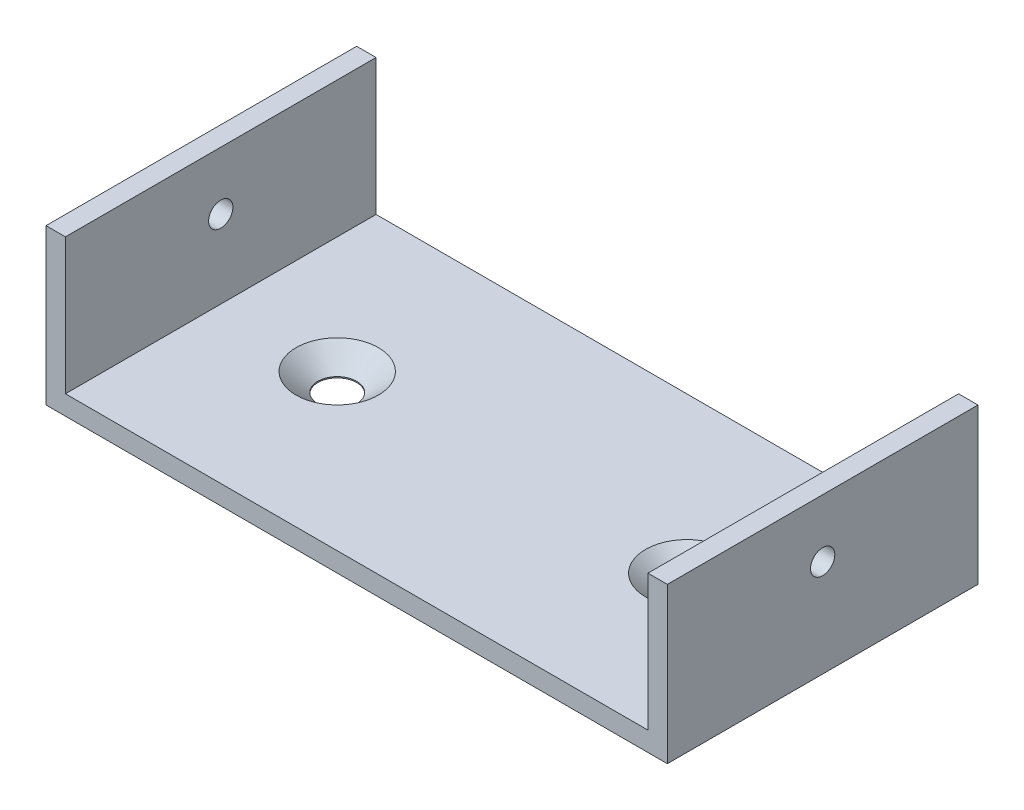
SolidWorks part; units mm, degrees
ref_plane "Front" through (0, 0, 0) normal (0, 0, 1) x (1, 0, 0)
ref_plane "Top" through (0, 0, 0) normal (0, 1, 0) x (1, 0, 0)
ref_plane "Right" through (0, 0, 0) normal (1, 0, 0) x (0, 0, -1)
sketch "Sketch1" plane through (0, 0, 0) normal (0, 0, 1) x (1, 0, 0)
  line L0 (0, -12.7) -> (0, 12.7) construction
  line L1 (-50.8, 0) -> (50.8, 0) construction
  line L2 (47.625, 12.7) -> (-47.625, 12.7) construction
  line L3 (-50.8, -12.7) -> (50.8, -12.7)
  line L4 (-50.8, -12.7) -> (-50.8, 12.7)
  line L5 (-50.8, 12.7) -> (50.8, 12.7)
  line L6 (50.8, -12.7) -> (50.8, 12.7)
  line L7 (-50.8, -12.7) -> (50.8, 12.7) construction
  line L8 (-50.8, 12.7) -> (50.8, -12.7) construction
  line L9 (-47.625, -12.7) -> (47.625, -12.7)
  point P3 (0, 0)
  point P4 (0, 0)
  point P8 (0, 0)
  point P13 (50.8, -9.525)
  point P17 (0, 12.7)
  point P20 (0, -12.7)
  dimension "Outside Width" = 101.6
  dimension "Outside Height" = 25.4
  dimension "Inside Height" = 22.225
  dimension "Wall Thickness" = 3.175
  dimension "Inside Width" = 95.25
sketch "Sketch2" plane through (0, 0, 0) normal (1, 0, 0) x (0, 0, -1)
  line L0 (-25.4, 0) -> (25.4, 0) construction
  dimension "Length" = 50.8
sketch "Sketch3" plane through (0, 0, 0) normal (0, 0, 1) x (1, 0, 0)
  line L0 (-50.8, 12.7) -> (-50.8, -12.7)
  line L1 (-50.8, -12.7) -> (50.8, -12.7)
  line L2 (50.8, -12.7) -> (50.8, 12.7)
  line L3 (50.8, 12.7) -> (47.625, 12.7)
  line L4 (47.625, 12.7) -> (47.625, -9.525)
  line L5 (47.625, -9.525) -> (-47.625, -9.525)
  line L6 (-47.625, -9.525) -> (-47.625, 12.7)
  line L7 (-47.625, 12.7) -> (-50.8, 12.7)
  line L8 (-47.625, -9.525) -> (-47.625, -12.7) construction
  dimension "D1" = 25.4
  dimension "D2" = 101.6
  dimension "D3" = 3.175
extrude "Boss-Extrude2" add sketch "Sketch3" along normal mid plane 50.8
sketch "Reference Sketch1" plane through (0, 0, 0) normal (1, 0, 0) x (0, 0, -1)
  line L0 (-25.4, 0) -> (25.4, 0) construction
  point P0 (19.05, 0)
  point P1 (-19.05, 0)
  dimension "D1" = 44.45
  dimension "D2" = 44.45
sketch "Sketch4" plane through (0, -9.525, 0) normal (0, 1, 0) x (1, 0, 0)
  line L0 (-47.625, 0) -> (-28.575, 0)
  line L1 (-47.625, -25.4) -> (-47.625, 25.4) construction
  line L2 (47.625, 0) -> (28.575, 0)
  line L3 (47.625, -25.4) -> (47.625, 25.4) construction
hole_wizard "1/4 (0.25) Diameter Hole1" positions "Sketch5" profile "Sketch6" hole size "1/4" standard "ANSI Inch" end condition through all
sketch "Sketch5" plane through (0, -9.525, 0) normal (0, 1, 0) x (1, 0, 0)
  point P0 (-28.575, 0)
  point P3 (28.575, 0)
sketch "Sketch6" plane through (-28.575, -9.525, 0) normal (1, 0, 0) x (0, 0, 1)
  line L0 (0, 0) -> (0, 3.175)
  line L1 (0, 3.175) -> (3.175, 3.175)
  line L2 (3.175, 3.175) -> (3.175, 2.9838)
  line L3 (3.175, 2.9838) -> (6.731, 0)
  line L5 (6.731, 0) -> (0, 0)
  line L6 (-3.175, 2.9838) -> (-6.731, 0) construction
  line L11 (0, -6.35) -> (0, 107.95) construction
  dimension "Thru Hole Dia." = 6.35
  dimension "Thru Hole Depth" = 3.175
  dimension "Near C'Sink Dia." = 13.462
  dimension "Near C'Sink Angle" = 100
sketch "Sketch7" plane through (50.8, 0, 0) normal (1, 0, 0) x (0, 0, -1)
  line L0 (0, -9.4842) -> (0, 3.2158)
hole_wizard "5/32 (0.15625) Diameter Hole1" positions "Sketch8" profile "Sketch9" hole size "5/32" standard "ANSI Inch" end condition through all
sketch "Sketch8" plane through (50.8, 0, 0) normal (1, 0, 0) x (0, 0, -1)
  point P0 (0, 3.2158)
sketch "Sketch9" plane through (50.8, 3.2158, 0) normal (0, 1, 0) x (0, 0, -1)
  line L0 (0, 0) -> (0, 101.6)
  line L1 (0, 101.6) -> (1.9844, 101.6)
  line L2 (1.9844, 101.6) -> (1.9844, 0)
  line L5 (1.9844, 0) -> (0, 0)
  line L11 (0, -6.35) -> (0, 107.95) construction
  dimension "Thru Hole Dia." = 3.9688
  dimension "Thru Hole Depth" = 101.6
equation "\"D1@Sketch3\" = \"Outside Height@Sketch1\""
equation "\"D2@Sketch3\" = \"Outside Width@Sketch1\""
equation "\"D3@Sketch3\" = \"Wall Thickness@Sketch1\""
equation "\"D1@Reference Sketch1\"=\"Outside Height@Sketch1\" * 1.75"
equation "\"D2@Reference Sketch1\" = \"D1@Reference Sketch1\""
equation "\"D1@Boss-Extrude2\" = \"Length@Sketch2\""
equation "\"Inside Height@Sketch1\"=\"Outside Height@Sketch1\"-\"Wall Thickness@Sketch1\""
equation "\"Inside Width@Sketch1\"=\"Outside Width@Sketch1\"-\"Wall Thickness@Sketch1\"*2"
